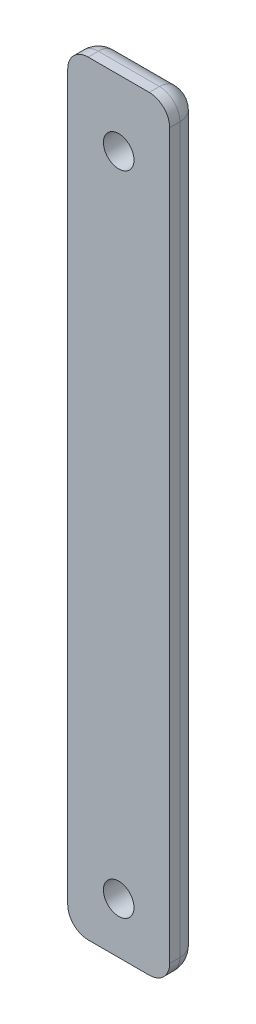
SolidWorks part; units mm, degrees
ref_plane "前视基准面" through (0, 0, 0) normal (0, 0, 1) x (1, 0, 0)
ref_plane "上视基准面" through (0, 0, 0) normal (0, 1, 0) x (1, 0, 0)
ref_plane "右视基准面" through (0, 0, 0) normal (1, 0, 0) x (0, 0, -1)
sketch "草图1" plane through (0, 0, 0) normal (0, 0, 1) x (1, 0, 0)
  line L1 (-5, 37.5) -> (5, 37.5)
  line L2 (-5, 37.5) -> (-5, -37.5)
  line L3 (-5, -37.5) -> (5, -37.5)
  line L4 (5, 37.5) -> (5, -37.5)
  line L5 (-5, 37.5) -> (5, -37.5) construction
  line L6 (-5, -37.5) -> (5, 37.5) construction
  point P0 (0, 0)
  dimension "D1" = 10
  dimension "D2" = 75
extrude "凸台-拉伸1" add sketch "草图1" along normal mid plane 3
fillet "圆角1" radius 2 8 edges at (0, 37.5, -1.5) (-5, 0, -1.5) (0, -37.5, -1.5) (5, 0, -1.5) (5, -37.5, 0) (-5, 37.5, 0) (-5, -37.5, 0) (5, 37.5, 0)
sketch "草图3" plane through (0, 0, 1.5) normal (0, 0, 1) x (1, 0, 0)
  line L1 (5, -35.5) -> (5, 35.5) construction
  line L3 (-3, -37.5) -> (3, -37.5) construction
  circle A0 centre (0, 31) radius 1.5
  circle A1 centre (0, -32.5) radius 1.5
  dimension "D1" = 63.5
  dimension "D2" = 5
  dimension "D3" = 5
  dimension "D4" = 5
extrude "切除-拉伸1" cut sketch "草图3" against normal blind 10
